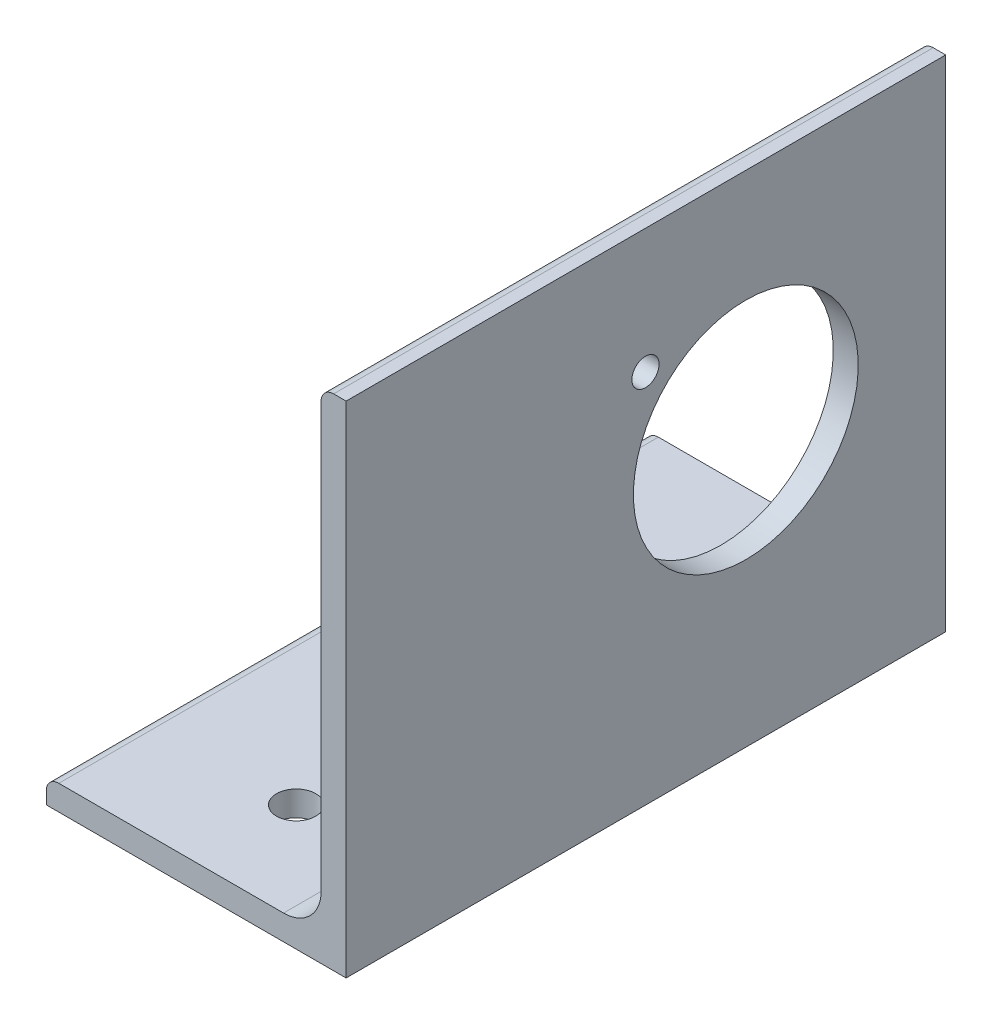
SolidWorks part; units mm, degrees
material "6061 Alloy"
ref_plane "Front Plane" through (0, 0, 0) normal (0, 0, 1) x (1, 0, 0)
ref_plane "Top Plane" through (0, 0, 0) normal (0, 1, 0) x (1, 0, 0)
ref_plane "Right Plane" through (0, 0, 0) normal (1, 0, 0) x (0, 0, -1)
sketch "Sketch0" plane through (0, 0, 0) normal (0, 0, 1) x (1, 0, 0)
  line L0 (-19.05, -31.75) -> (19.05, -31.75)
  line L1 (19.05, -31.75) -> (19.05, 31.75)
  line L2 (19.05, 0) -> (0, 0) construction
  line L3 (0, 0) -> (0, -31.75) construction
  line L4 (15.875, -23.7998) -> (15.875, 31.75) construction
  line L5 (11.0998, -28.575) -> (-19.05, -28.575) construction
  arc A0 (15.875, -23.7998) -> (11.0998, -28.575) centre (11.0998, -23.7998) cw
  point P3 (14.4764, -27.1764)
  dimension "Inside Corner Radius" = 4.7752
  dimension "Outside Height" = 63.5
  dimension "Inside Height" = 60.325
  dimension "Inside Width" = 34.925
  dimension "Wall Thickness" = 3.175
  dimension "D1" = 3.175
  dimension "Outside Width" = 38.1
sketch "Sketch1" plane through (0, 0, 0) normal (1, 0, 0) x (0, 0, -1)
  line L0 (38.1, 0) -> (-38.1, 0)
  point P4 (0, 0)
  dimension "Length" = 76.2
sketch "Sketch2" plane through (0, 0, 0) normal (0, 0, 1) x (1, 0, 0)
  line L0 (-19.05, -31.75) -> (19.05, -31.75)
  line L1 (19.05, -31.75) -> (19.05, 31.75)
  line L2 (19.05, 31.75) -> (15.875, 31.75) construction
  line L3 (15.875, 30.1625) -> (15.875, -23.7998)
  line L4 (11.0998, -28.575) -> (-17.4625, -28.575)
  line L5 (-19.05, -31.75) -> (-19.05, -28.575) construction
  line L6 (17.4625, 31.75) -> (19.05, 31.75)
  line L7 (-19.05, -30.1625) -> (-19.05, -31.75)
  line L8 (19.05, 0) -> (0, 0) construction
  line L9 (0, 0) -> (0, -31.75) construction
  arc A0 (15.875, 30.1625) -> (17.4625, 31.75) centre (17.4625, 30.1625) cw
  arc A1 (-19.05, -30.1625) -> (-17.4625, -28.575) centre (-17.4625, -30.1625) cw
  arc A2 (15.875, -23.7998) -> (11.0998, -28.575) centre (11.0998, -23.7998) cw
  dimension "Inside Radius" = 4.7752
  dimension "Height" = 63.5
  dimension "Width" = 38.1
  dimension "Thickness" = 3.175
extrude "Boss-Extrude1" add sketch "Sketch2" along normal mid plane 76.2
sketch "Break Locations" plane through (0, 0, 0) normal (1, 0, 0) x (0, 0, -1)
  line L0 (26.67, 0) -> (-26.67, 0)
  line L1 (-38.1, -31.75) -> (-38.1, 31.75) construction
  line L2 (38.1, -31.75) -> (38.1, 31.75) construction
  point P0 (15.875, 0)
  point P1 (-15.875, 0)
  point P10 (0, 0)
  point P11 (-26.67, 0)
  point P13 (26.67, 0)
  dimension "D1" = 53.975
  dimension "D2" = 53.975
  dimension "D3" = 64.77
sketch "Sketch3" plane through (15.875, 0, 0) normal (-1, 0, 0) x (0, 0, 1)
  line L0 (-12.7, 3.1782) -> (0.052, 15.9301) construction
  line L1 (-12.7, 3.1782) -> (-38.1, 3.1813) construction
  line L3 (-38.1, 30.1625) -> (-38.1, -23.7998) construction
  circle A0 centre (-12.7, 3.1782) radius 14.2875
  circle A1 centre (0.052, 15.9301) radius 1.7272
  dimension "D1" = 25.4
extrude "Cut-Extrude1" cut sketch "Sketch3" against normal through all
sketch "Sketch9" plane through (0, -31.75, 0) normal (0, -1, 0) x (1, 0, 0)
  line L0 (19.05, 12.7) -> (0, 12.7) construction
  line L2 (0, 12.7) -> (0, 25.4) construction
  line L3 (0, 12.7) -> (0, 0) construction
  circle A0 centre (0, 25.4) radius 2.4892
  circle A1 centre (0, 0) radius 2.4892
  dimension "D1" = 19.05
  dimension "D2" = 25.4
  dimension "D3" = 25.4
extrude "Cut-Extrude2" cut sketch "Sketch9" against normal through all
equation "\"D1@Break Locations\" = .85 * \"Height@Sketch2\""
equation "\"D2@Break Locations\"=\"D1@Break Locations\""
equation "\"Thickness@Sketch2\"=\"wall thickness@sketch0\""
equation "\"Height@Sketch2\"=\"outside height@sketch0\""
equation "\"Width@Sketch2\"=\"outside width@sketch0\""
equation "\"Inside Radius@Sketch2\"=\"inside corner radius@sketch0\""
equation "\"Length@Boss-Extrude1\"=\"length@sketch1\""
equation "\"D3@Break Locations\"=\"D2@Break Locations\"*1.2"
equation "\"D1@Sketch0\"=\"Wall Thickness@Sketch0\""
